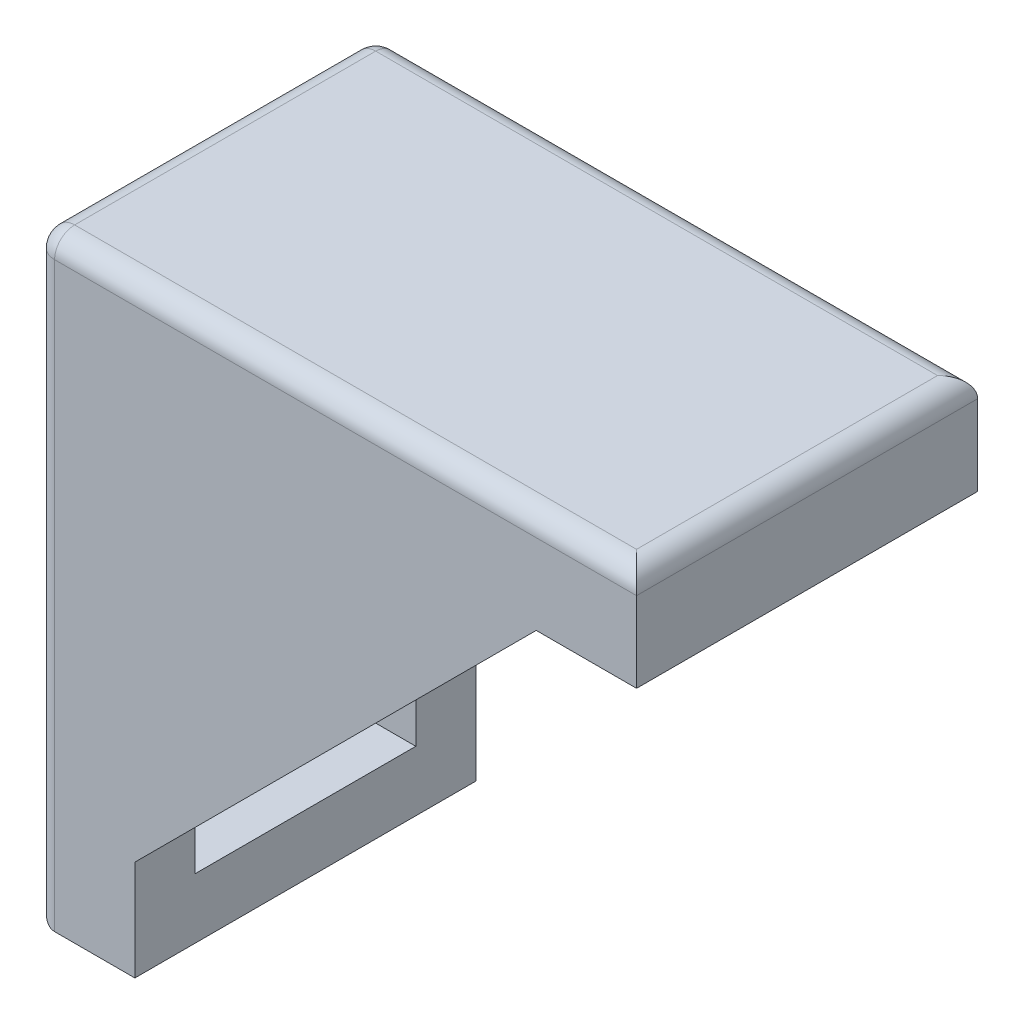
SolidWorks part; units mm, degrees
ref_plane "Front Plane" through (0, 0, 0) normal (0, 0, 1) x (1, 0, 0)
ref_plane "Top Plane" through (0, 0, 0) normal (0, 1, 0) x (1, 0, 0)
ref_plane "Right Plane" through (0, 0, 0) normal (1, 0, 0) x (0, 0, -1)
sketch "Sketch1" plane through (0, 0, 0) normal (0, 0, 1) x (1, 0, 0)
  line L0 (0, 0) -> (30, 0)
  line L2 (0, -30) -> (0, 0)
  line L3 (30, 0) -> (30, -5)
  line L4 (30, -5) -> (25, -5)
  line L5 (25, -5) -> (5, -25)
  line L6 (5, -25) -> (5, -30)
  line L7 (5, -30) -> (0, -30)
  dimension "D1" = 30
  dimension "D2" = 30
  dimension "D3" = 5
  dimension "D4" = 5
  dimension "D5" = 5
  dimension "D6" = 5
extrude "Boss-Extrude1" add sketch "Sketch1" against normal blind 17
fillet "Fillet1" radius 1 7 edges at (0, -30, -8.5) (0, -15, -17) (0, 0, -8.5) (15, 0, -17) (30, 0, -8.5) (0, -15, 0) (15, 0, 0)
shell "Shell1" thickness 3
